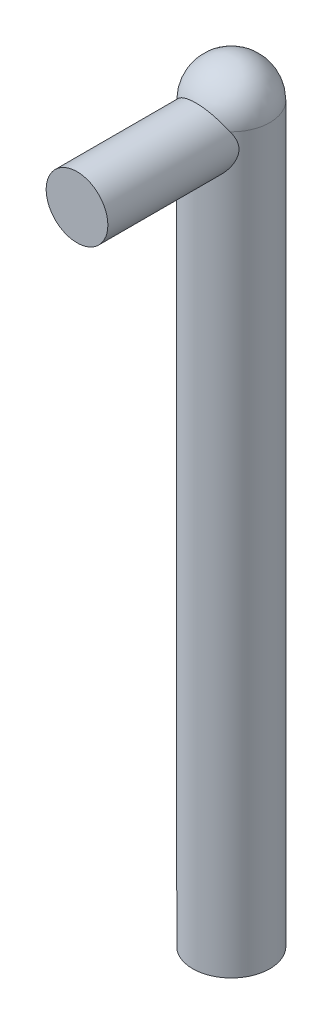
SolidWorks part; units mm, degrees
ref_plane "前视基准面" through (0, 0, 0) normal (0, 0, 1) x (1, 0, 0)
ref_plane "上视基准面" through (0, 0, 0) normal (0, 1, 0) x (1, 0, 0)
ref_plane "右视基准面" through (0, 0, 0) normal (1, 0, 0) x (0, 0, -1)
sketch "草图1" plane through (0, 0, 0) normal (0, 1, 0) x (1, 0, 0)
  circle A0 centre (0, 0) radius 25
  dimension "D1" = 50
extrude "凸台-拉伸1" add sketch "草图1" along normal blind 500
fillet "圆角1" radius 25 1 edges at (0, 500, 25)
sketch "草图3" plane through (0, 0, 0) normal (0, 0, 1) x (1, 0, 0)
  line L1 (-25, 475) -> (25, 475) construction
  line L4 (-25, 475) -> (-25, 0) construction
  line L6 (0, 475) -> (0, 465) construction
  circle A1 centre (0, 465) radius 20
  dimension "D1" = 50
  dimension "D3" = 40
  dimension "D2" = 10
extrude "凸台-拉伸2" add sketch "草图3" along normal blind 100
